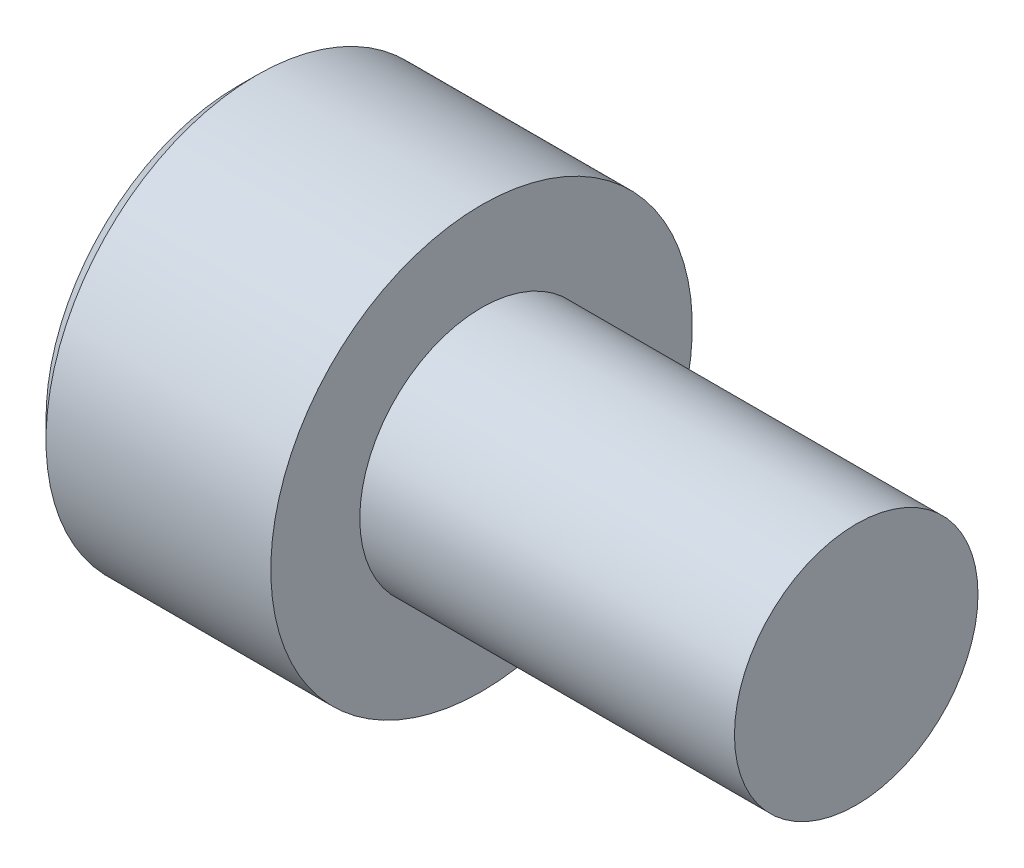
SolidWorks part; units mm, degrees
material "SUS304相当"
ref_plane "Front Plane" through (0, 0, 0) normal (0, 0, 1) x (1, 0, 0)
ref_plane "Top Plane" through (0, 0, 0) normal (0, 1, 0) x (1, 0, 0)
ref_plane "Right Plane" through (0, 0, 0) normal (1, 0, 0) x (0, 0, -1)
sketch "Sketch1" plane through (0, 0, 0) normal (0, 0, 1) x (1, 0, 0)
  line L0 (-2.6, 0) -> (4, 0) construction
  line L1 (0, 1.3) -> (4, 1.3)
  line L3 (-2.6, 0) -> (4, 0)
  line L4 (4, 1.3) -> (4, 0)
  line L6 (0, 1.3) -> (0, 2.25)
  line L7 (0, 2.25) -> (-2.6, 2.25)
  line L8 (-2.6, 0) -> (-2.6, 2.25)
  dimension "L" = 4
  dimension "M" = 2.6
  dimension "E" = 2.6
  dimension "A" = 4.5
revolve "Revolve1" add sketch "Sketch1" about L0
cosmetic thread "Thread1" parameters "L_s"=4, "ATD"=2.1129
sketch "Sketch2" plane through (0, 0, 0) normal (0, 0, 1) x (1, 0, 0)
  line L0 (-2.6, 0) -> (-0.8991, 0) construction
  line L1 (-2.6, 0) -> (4, 0) construction
  line L2 (-0.8991, 0) -> (-1.5, 1)
  line L3 (-1.5, 1) -> (-2.6, 1)
  line L4 (-2.6, 0) -> (-2.6, 2.25) construction
  line L5 (-2.6, 1) -> (-2.6, 0)
  line L6 (-2.6, 0) -> (-0.8991, 0)
  dimension "MSM_1" = 1.1
  dimension "FIX_2" = 59
revolve "Cut-Revolve1" cut sketch "Sketch2" about L0
sketch "Sketch3" plane through (-2.6, 0, 0) normal (-1, 0, 0) x (0, 0, 1)
  line L0 (0, -2.475) -> (0, 2.475) construction
  line L1 (1, 0.5774) -> (0, 1.1547)
  line L2 (0, 1.1547) -> (-1, 0.5774)
  line L3 (-1, 0.5774) -> (-1, -0.5774)
  line L4 (-1, -0.5774) -> (0, -1.1547)
  line L5 (0, -1.1547) -> (1, -0.5774)
  line L6 (1, -0.5774) -> (1, 0.5774)
  circle A0 centre (0, 0) radius 1 construction
extrude "Cut-Extrude1" cut sketch "Sketch3" against normal blind 1.1
chamfer "Chamfer1" distance 0.2 1 edges at (-2.6, -2.25, 0)
